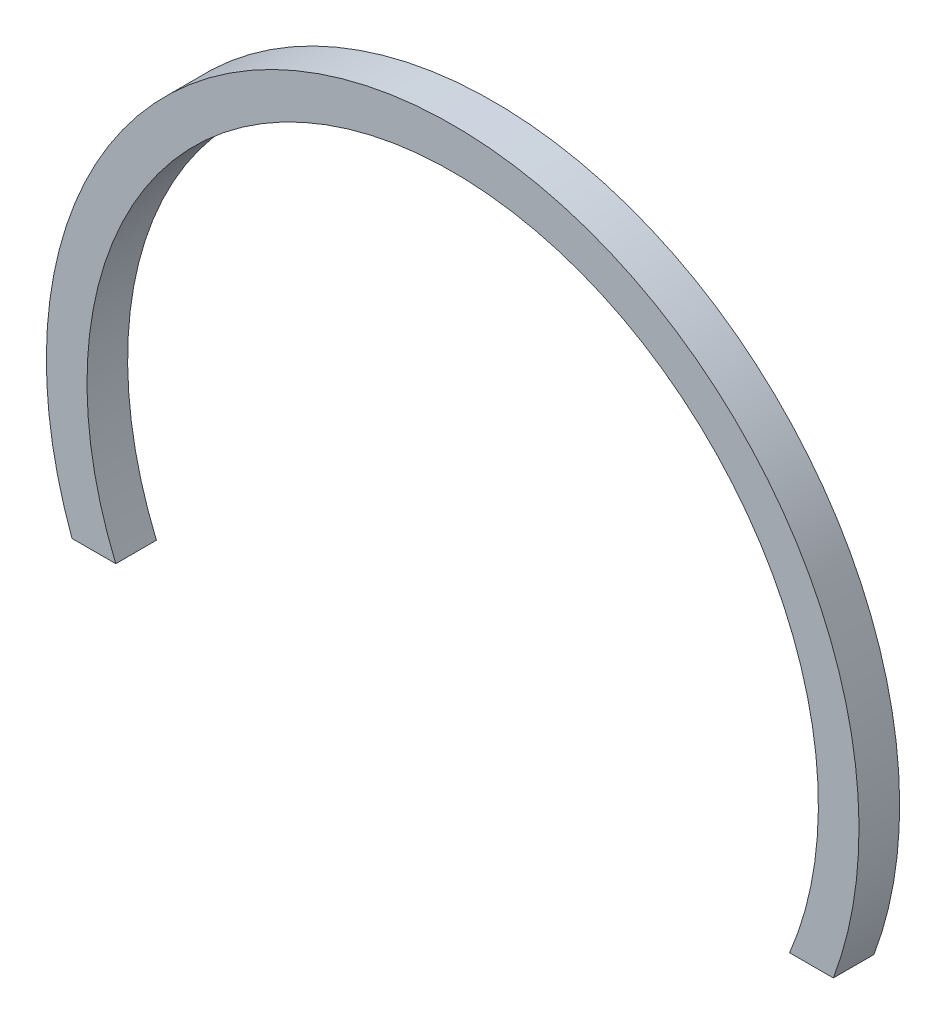
SolidWorks part; units mm, degrees
ref_plane "Front Plane" through (0, 0, 0) normal (0, 0, 1) x (1, 0, 0)
ref_plane "Top Plane" through (0, 0, 0) normal (0, 1, 0) x (1, 0, 0)
ref_plane "Right Plane" through (0, 0, 0) normal (1, 0, 0) x (0, 0, -1)
sketch "Sketch1" plane through (0, 0, 0) normal (0, 0, 1) x (1, 0, 0)
  circle A0 centre (0, 0) radius 30
extrude "Arch_Outer" add sketch "Sketch1" along normal blind 3 from offset 0
sketch "Sketch2" plane through (0, 0, 0) normal (0, 0, 1) x (1, 0, 0)
  circle A0 centre (0, 0) radius 27
extrude "Wheel_Clearance_R27" cut sketch "Sketch2" along normal blind 3.2 from offset 0.1
sketch "Sketch3" plane through (0, 0, 0) normal (0, 0, 1) x (1, 0, 0)
  line L1 (-31, -31) -> (31, -31)
  line L2 (-31, -31) -> (-31, -10.5)
  line L3 (-31, -10.5) -> (31, -10.5)
  line L4 (31, -31) -> (31, -10.5)
extrude "Open_Bottom_At_Ground_Clearance" cut sketch "Sketch3" along normal blind 3.2 from offset 0.1
